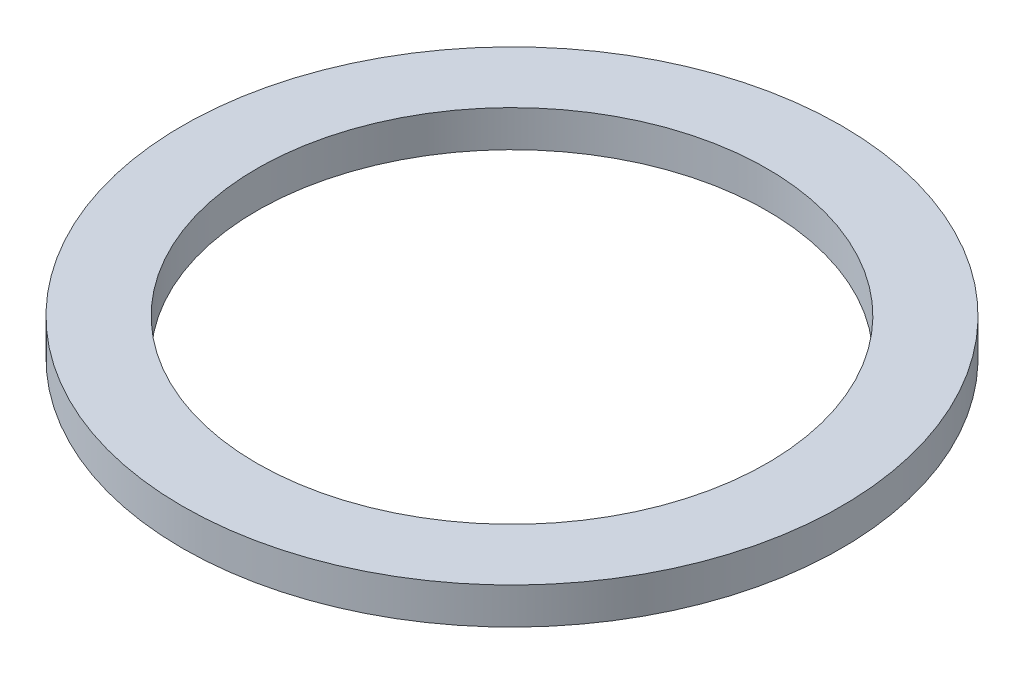
SolidWorks part; units mm, degrees
ref_plane "Front Plane" through (0, 0, 0) normal (0, 0, 1) x (1, 0, 0)
ref_plane "Top Plane" through (0, 0, 0) normal (0, 1, 0) x (1, 0, 0)
ref_plane "Right Plane" through (0, 0, 0) normal (1, 0, 0) x (0, 0, -1)
sketch "Sketch1" plane through (0, 0, 0) normal (0, 1, 0) x (1, 0, 0)
  circle A1 centre (0, 0) radius 14.351
extrude "Boss-Extrude1" add sketch "Sketch1" along normal blind 1.5875 contours A1
sketch "Sketch2" plane through (0, 1.5875, 0) normal (0, 1, 0) x (1, 0, 0)
  circle A0 centre (0, 0) radius 11.1125
extrude "Cut-Extrude1" cut sketch "Sketch2" against normal through all
